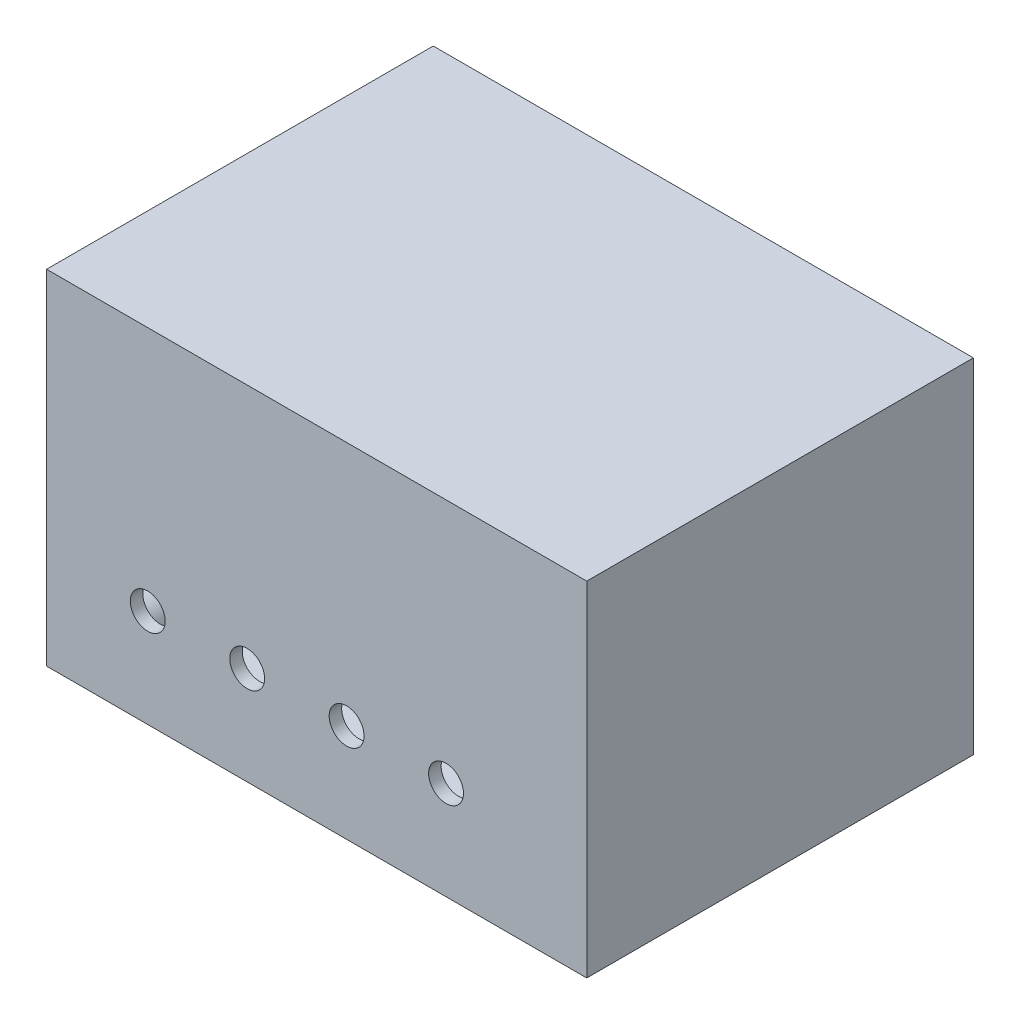
SolidWorks part; units mm, degrees
ref_plane "Front Plane" through (0, 0, 0) normal (0, 0, 1) x (1, 0, 0)
ref_plane "Top Plane" through (0, 0, 0) normal (0, 1, 0) x (1, 0, 0)
ref_plane "Right Plane" through (0, 0, 0) normal (1, 0, 0) x (0, 0, -1)
sketch "Sketch1" plane through (0, 0, 0) normal (0, 0, 1) x (1, 0, 0)
  line L1 (-58.1808, 27.5798) -> (51.8192, 27.5798)
  line L2 (-58.1808, 27.5798) -> (-58.1808, -42.4202)
  line L3 (-58.1808, -42.4202) -> (51.8192, -42.4202)
  line L4 (51.8192, 27.5798) -> (51.8192, -42.4202)
  dimension "D1" = 110
  dimension "D2" = 70
extrude "Boss-Extrude1" add sketch "Sketch1" along normal blind 2.54
sketch "Sketch4" plane through (0, 0, 0) normal (0, 0, -1) x (-1, 0, 0)
  line L0 (55.6808, -39.9202) -> (55.6808, 25.0798)
  line L1 (55.6808, 25.0798) -> (-49.3192, 25.0798)
  line L2 (-49.3192, 25.0798) -> (-49.3192, -39.9202)
  line L3 (-49.3192, -39.9202) -> (55.6808, -39.9202)
  line L4 (58.1808, -42.4202) -> (58.1808, 27.5798)
  line L5 (58.1808, 27.5798) -> (-51.8192, 27.5798)
  line L6 (-51.8192, 27.5798) -> (-51.8192, -42.4202)
  line L7 (-51.8192, -42.4202) -> (58.1808, -42.4202)
  line L8 (58.1808, -42.4202) -> (58.1808, 27.5798)
  line L9 (58.1808, 27.5798) -> (-51.8192, 27.5798)
  line L10 (-51.8192, 27.5798) -> (-51.8192, -42.4202)
  line L11 (-51.8192, -42.4202) -> (58.1808, -42.4202)
  dimension "D1" = 0
  dimension "D2" = 2.5
extrude "Boss-Extrude3" add sketch "Sketch4" along normal blind 76.2
sketch "Sketch7" plane through (0, 0, 0) normal (0, 0, -1) x (-1, 0, 0)
  circle A0 centre (47.1808, -32.4202) radius 1.5 construction
  circle A1 centre (-43.8192, -32.4202) radius 1.5
  circle A2 centre (-43.8192, -32.4202) radius 1.5
  circle A3 centre (-43.8192, 17.5798) radius 1.5
  circle A4 centre (-43.8192, 17.5798) radius 1.5
  circle A5 centre (47.1808, -32.4202) radius 1.5
  circle A6 centre (47.1808, 17.5798) radius 1.5 construction
  circle A7 centre (47.1808, 17.5798) radius 1.5
  circle A8 centre (-43.8192, 17.5798) radius 5.31
  circle A9 centre (47.1808, 17.5798) radius 5.31
  circle A10 centre (47.1808, -32.4202) radius 5.31
  circle A11 centre (-43.8192, -32.4202) radius 5.31
  circle A12 centre (-43.8192, 17.5798) radius 2.77
  circle A13 centre (47.1808, 17.5798) radius 2.77
  circle A14 centre (-43.8192, -32.4202) radius 2.77
  circle A15 centre (47.1808, -32.4202) radius 2.77
  dimension "D1" = 1.27
  dimension "D2" = 0
  dimension "D3" = 0
  dimension "D4" = 3.81
extrude "Boss-Extrude5" add sketch "Sketch7" along normal blind 10 contours A8 A12 | A9 A13 | A10 A15 | A11 A14
sketch "Sketch9" plane through (0, 0, 2.54) normal (0, 0, 1) x (1, 0, 0)
  circle A0 centre (23.1692, -22.4202) radius 3.55 construction
  circle A1 centre (2.9192, -22.4202) radius 3.55 construction
  circle A2 centre (-17.3308, -22.4202) radius 3.55 construction
  circle A3 centre (-37.5808, -22.4202) radius 3.55 construction
  circle A4 centre (23.1692, -22.4202) radius 3.55
  circle A5 centre (2.9192, -22.4202) radius 3.55
  circle A6 centre (-17.3308, -22.4202) radius 3.55
  circle A7 centre (-37.5808, -22.4202) radius 3.55
extrude "Cut-Extrude1" cut sketch "Sketch9" against normal blind 2.54
